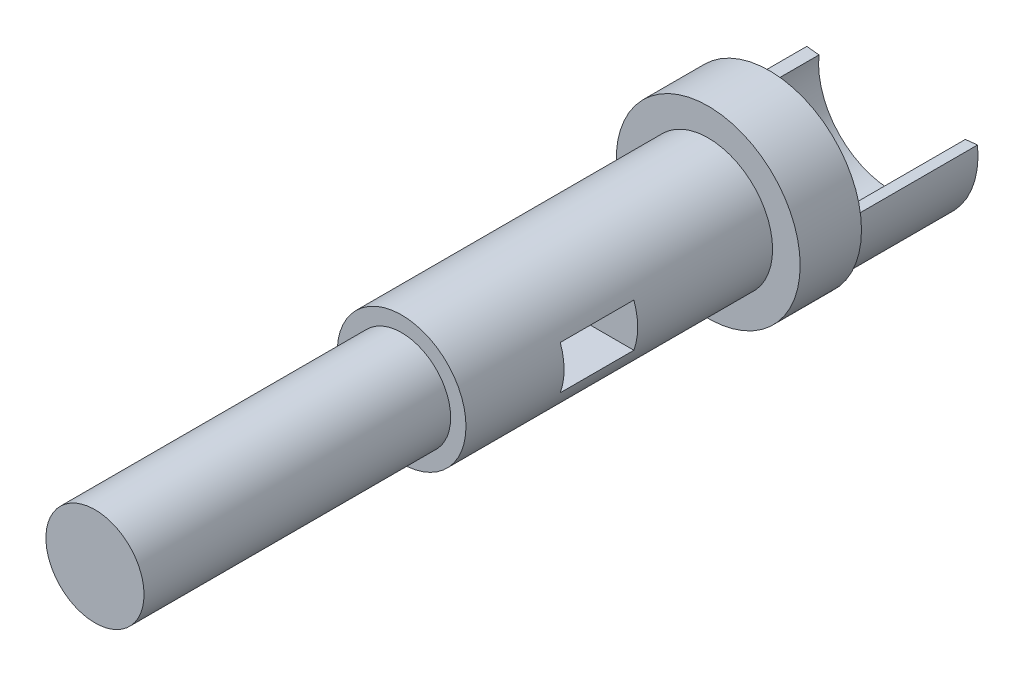
SolidWorks part; units mm, degrees
ref_plane "Front Plane" through (0, 0, 0) normal (0, 0, 1) x (1, 0, 0)
ref_plane "Top Plane" through (0, 0, 0) normal (0, 1, 0) x (1, 0, 0)
ref_plane "Right Plane" through (0, 0, 0) normal (1, 0, 0) x (0, 0, -1)
sketch "Sketch2" plane through (0, 0, 0) normal (0, 1, 0) x (1, 0, 0)
  line L0 (0, 0) -> (0, 110) construction
  line L1 (0, 0) -> (8, 0)
  line L2 (8, 0) -> (8, 50)
  line L3 (8, 50) -> (10.5, 50)
  line L4 (10.5, 50) -> (10.5, 100)
  line L5 (10.5, 100) -> (15, 100)
  line L6 (15, 100) -> (15, 110)
  line L7 (0, 110) -> (15, 110)
  line L8 (0, 0) -> (0, 110)
  dimension "D1" = 50
  dimension "D2" = 50
  dimension "D3" = 10
  dimension "D4" = 15
  dimension "D5" = 10.5
  dimension "D6" = 8
revolve "Revolve4" add sketch "Sketch2" angle 360 about L0
sketch "Sketch3" plane through (0, 0, -110) normal (0, 0, -1) x (-1, 0, 0)
  line L0 (-14, 0) -> (14, 0) construction
  line L1 (-11.9343, 1.2543) -> (-13.9233, 1.4634)
  line L2 (11.9343, 1.2543) -> (13.9233, 1.4634)
  circle A0 centre (0, 0) radius 12
  circle A1 centre (0, 0) radius 14
  dimension "D1" = 24
  dimension "D2" = 28
  dimension "D3" = 6
  dimension "D4" = 6
extrude "Boss-Extrude3" add sketch "Sketch3" along normal blind 20 contours A1 L0 A0 L1 | L0 A1 A0 | A0 L0 A1 L2
sketch "Sketch4" plane through (0, 0, 0) normal (1, 0, 0) x (0, 0, -1)
  line L0 (50, 0) -> (100, 0) construction
  line L1 (50, 8) -> (50, -8) construction
  line L2 (100, 10.5) -> (100, -10.5) construction
  line L3 (66, -3.55) -> (66, 3.55)
  line L4 (66, 3.55) -> (78, 3.55)
  line L5 (78, 3.55) -> (78, -3.55)
  line L6 (50, 10.5) -> (50, -10.5) construction
  line L7 (66, -3.55) -> (78, -3.55)
  point P13 (78, 0)
  point P14 (66, 0)
  dimension "D1" = 12
  dimension "D2" = 3.55
  dimension "D3" = 16
extrude "Cut-Extrude1" cut sketch "Sketch4" along normal through all
